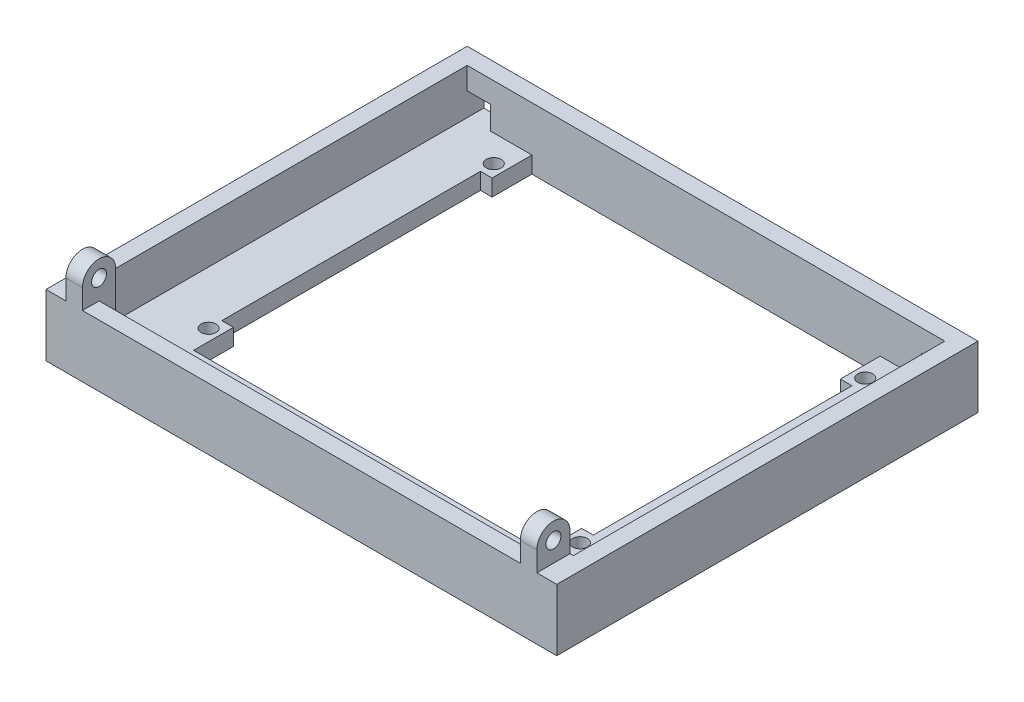
SolidWorks part; units mm, degrees
ref_plane "Front Plane" through (0, 0, 0) normal (0, 0, 1) x (1, 0, 0)
ref_plane "Top Plane" through (0, 0, 0) normal (0, 1, 0) x (1, 0, 0)
ref_plane "Right Plane" through (0, 0, 0) normal (1, 0, 0) x (0, 0, -1)
sketch "Sketch1" plane through (0, 0, 0) normal (0, 1, 0) x (1, 0, 0)
  line L1 (52.5, -51) -> (-52.5, -51)
  line L2 (52.5, -51) -> (52.5, 51)
  line L3 (52.5, 51) -> (-52.5, 51)
  line L4 (-52.5, -51) -> (-52.5, 51)
  line L5 (52.5, -51) -> (-52.5, 51) construction
  line L6 (52.5, 51) -> (-52.5, -51) construction
  line L7 (77, 56) -> (-77, 56)
  line L8 (77, 56) -> (77, -56)
  line L9 (77, -56) -> (-77, -56)
  line L10 (-77, 56) -> (-77, -56)
  line L11 (77, 56) -> (-77, -56) construction
  line L12 (77, -56) -> (-77, 56) construction
  line L13 (-56, 39) -> (56, 39)
  line L14 (-56, 39) -> (-56, -39)
  line L15 (-56, -39) -> (56, -39)
  line L16 (56, 39) -> (56, -39)
  line L17 (-56, 39) -> (56, -39) construction
  line L18 (-56, -39) -> (56, 39) construction
  line L19 (77, -56) -> (-77, -56)
  line L20 (77, -56) -> (77, -71)
  line L21 (77, -71) -> (-77, -71)
  line L22 (-77, -56) -> (-77, -71)
  circle A0 centre (-56, 43) radius 2.25
  circle A1 centre (56, 43) radius 2.25
  circle A2 centre (56, -43) radius 2.25
  circle A3 centre (-56, -43) radius 2.25
  point P0 (0, 0)
  point P8 (0, 0)
  point P13 (0, 0)
  dimension "D7" = 4.5
  dimension "D1" = 43
  dimension "D2" = 56
  dimension "D5" = 102
  dimension "D6" = 105
  dimension "D8" = 112
  dimension "D9" = 77
  dimension "D10" = 86
  dimension "D11" = 112
  dimension "D12" = 78
  dimension "D13" = 127
  dimension "D3" = 2
  dimension "D4" = 2
extrude "Boss-Extrude1" add sketch "Sketch1" along normal blind 5 contours L7 L10 L9 L8 A3 A2 A1 A0 L13 L16 L15 L2 L1 L4 L14 L3 | L9 L22 L21 L20
sketch "Sketch2" plane through (-77, 0, 0) normal (-1, 0, 0) x (0, 0, 1)
  line L0 (-56, 5) -> (71, 5) construction
  line L1 (61, 24.65) -> (61, 0)
  line L3 (-56, 0) -> (71, 0) construction
  line L4 (71, 24.65) -> (71, 0)
  line L5 (71, 0) -> (61, 0)
  line L6 (-56, 5) -> (71, 5) construction
  circle A0 centre (66, 24.65) radius 2.25
  arc A1 (71, 24.65) -> (61, 24.65) centre (66, 24.65) ccw
  dimension "D1" = 4.5
  dimension "D2" = 19.65
  dimension "D3" = 66
  dimension "D4" = 5
  dimension "D5" = 0
  dimension "D6" = 19.65
  dimension "D7" = 10
extrude "Boss-Extrude2" add sketch "Sketch2" against normal blind 11
sketch "Sketch4" plane through (0, 5, 0) normal (0, 1, 0) x (1, 0, 0)
  line L0 (-77, 56) -> (-77, -61) construction
  line L1 (-71, -61) -> (-77, -61)
  line L2 (-71, -61) -> (-71, -71)
  line L3 (-71, -71) -> (-77, -71)
  line L4 (-77, -61) -> (-77, -71)
  line L5 (77, -71) -> (-66, -71) construction
  line L6 (-66, -61) -> (-77, -61) construction
  dimension "D1" = 0
  dimension "D2" = 0
  dimension "D3" = 6
  dimension "D4" = 0
extrude "Cut-Extrude1" cut sketch "Sketch4" along normal blind 37
mirror "Mirror1" about plane through (0, 0, 0) normal (1, 0, 0) of "Cut-Extrude1", "Boss-Extrude2"
sketch "Sketch5" plane through (0, 5, 0) normal (0, 1, 0) x (1, 0, 0)
  line L1 (77, -71) -> (-77, -71)
  line L2 (77, -71) -> (77, 56)
  line L3 (77, 56) -> (-77, 56)
  line L4 (-77, -71) -> (-77, 56)
  line L5 (72, -66) -> (-72, -66)
  line L6 (72, -66) -> (72, 51)
  line L7 (72, 51) -> (-72, 51)
  line L8 (-72, -66) -> (-72, 51)
  line L9 (66, -61) -> (72, -61)
  line L10 (66, -61) -> (66, -66)
  line L11 (66, -66) -> (72, -66)
  line L12 (72, -61) -> (72, -66)
  line L13 (-66, -61) -> (-72, -61)
  line L14 (-66, -61) -> (-66, -66)
  line L15 (-66, -66) -> (-72, -66)
  line L16 (-72, -61) -> (-72, -66)
  line M23 (-52.5, 51) -> (52.5, 51)
  line M25 (66, -71) -> (66, -61)
  line M27 (71, -61) -> (71, -71)
  line M28 (71, -71) -> (77, -71)
  line M29 (77, -71) -> (77, 56)
  line M30 (77, 56) -> (-77, 56)
  line M31 (-77, 56) -> (-77, -71)
  line M32 (-77, -71) -> (-71, -71)
  line M33 (-71, -71) -> (-71, -61)
  line M35 (-66, -61) -> (-66, -71)
  line M36 (-66, -71) -> (66, -71)
  dimension "D1" = 5
  dimension "D2" = 5
  dimension "D3" = 5
  dimension "D4" = 5
extrude "Boss-Extrude3" add sketch "Sketch5" along normal blind 13.65 contours L5 L8 L7 L6 M23 M27 M28 M29 M30 M31 M32 M33 | L5 M25 M35 M36 | L9 L5 L6 M27 | L16 L13 L14 L15
sketch "Sketch6" plane through (0, 0, -51) normal (0, 0, 1) x (1, 0, 0)
  line L1 (72, 5) -> (65, 5)
  line L2 (72, 5) -> (72, 12)
  line L3 (72, 12) -> (65, 12)
  line L4 (65, 5) -> (65, 12)
  dimension "D1" = 7
  dimension "D2" = 7
extrude "Cut-Extrude2" cut sketch "Sketch6" against normal blind 13.65
mirror "Mirror2" about plane through (0, 0, 0) normal (1, 0, 0) of "Cut-Extrude2"
